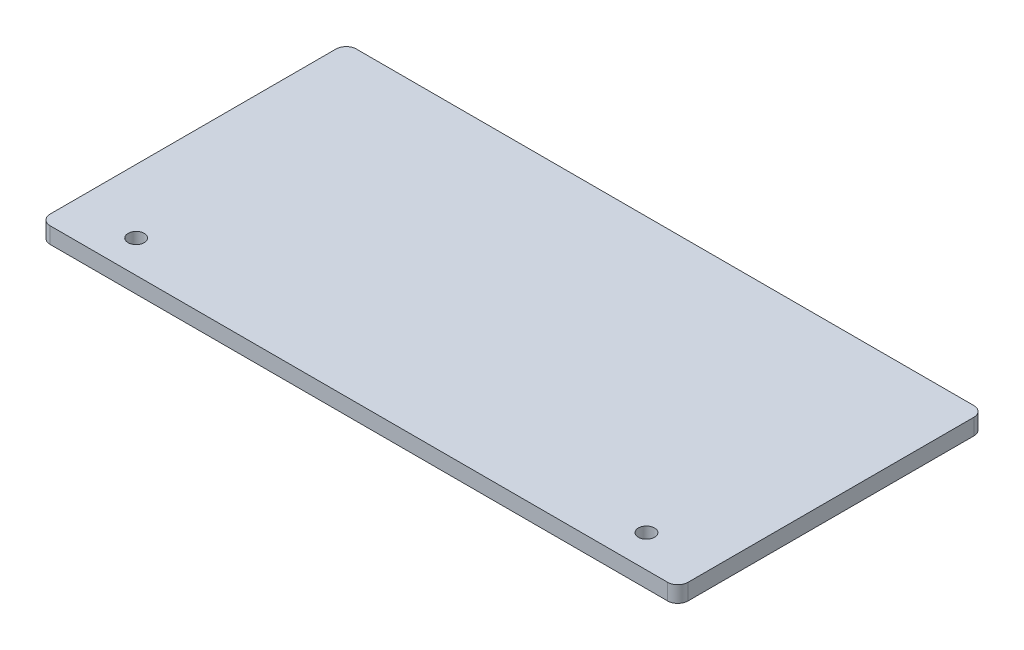
SolidWorks part; units mm, degrees
ref_plane "Front Plane" through (0, 0, 0) normal (0, 0, 1) x (1, 0, 0)
ref_plane "Top Plane" through (0, 0, 0) normal (0, 1, 0) x (1, 0, 0)
ref_plane "Right Plane" through (0, 0, 0) normal (1, 0, 0) x (0, 0, -1)
sketch "Sketch1" plane through (0, 0, 0) normal (0, 1, 0) x (1, 0, 0)
  line L0 (-62.5, -47.3) -> (62.5, -47.3) construction
  line L1 (-60.5, 0) -> (60.5, 0)
  line L2 (-62.5, -2) -> (-62.5, -58)
  line L3 (-60.5, -60) -> (60.5, -60)
  line L4 (62.5, -2) -> (62.5, -58)
  line L5 (-62.5, -12.7) -> (62.5, -12.7) construction
  arc A0 (-62.5, -58) -> (-60.5, -60) centre (-60.5, -58) ccw
  arc A1 (60.5, -60) -> (62.5, -58) centre (60.5, -58) ccw
  arc A2 (60.5, 0) -> (62.5, -2) centre (60.5, -2) cw
  arc A3 (-60.5, 0) -> (-62.5, -2) centre (-60.5, -2) ccw
  circle A6 centre (-50, -53.65) radius 1.5875
  circle A7 centre (50, -53.65) radius 1.5875
  point P7 (-62.5, -60)
  point P12 (62.5, 0)
  point P15 (-62.5, 0)
  dimension "D3" = 2
  dimension "D10" = 3.175
  dimension "D11" = 6.35
  dimension "D1" = 125
  dimension "D2" = 60
  dimension "D4" = 12.7
  dimension "D5" = 12.7
  dimension "D12" = 100
  dimension "D13" = 12.5
extrude "Boss-Extrude1" add sketch "Sketch1" along normal blind 3.175
